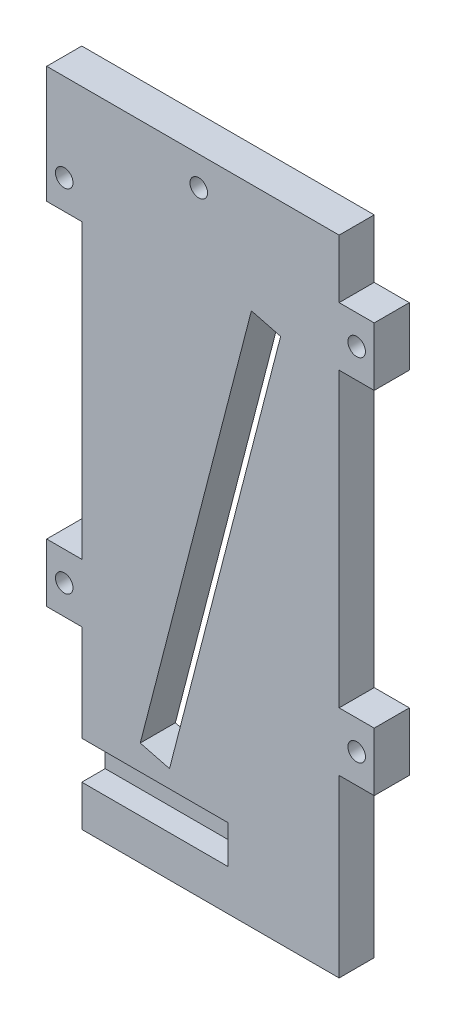
SolidWorks part; units mm, degrees
ref_plane "Plan de face" through (0, 0, 0) normal (0, 0, 1) x (1, 0, 0)
ref_plane "Plan de dessus" through (0, 0, 0) normal (0, 1, 0) x (1, 0, 0)
ref_plane "Plan de droite" through (0, 0, 0) normal (1, 0, 0) x (0, 0, -1)
sketch "Esquisse1" plane through (0, 0, 0) normal (0, 0, 1) x (1, 0, 0)
  line L0 (-6, 90) -> (-6, 70)
  line L1 (0, 0) -> (44, 0)
  line L2 (0, 0) -> (0, 10)
  line L3 (-6, 90) -> (44, 90)
  line L4 (44, 0) -> (44, 10)
  line L6 (44, 80) -> (44, 90)
  line L7 (0, 70) -> (-6, 70)
  line L9 (44, 80) -> (50, 80)
  line L10 (44, 20) -> (44, 70)
  line L11 (44, 70) -> (50, 70)
  line L12 (50, 80) -> (50, 70)
  line L13 (44, 10) -> (50, 10)
  line L14 (0, 20) -> (0, 70)
  line L15 (44, 20) -> (50, 20)
  line L16 (50, 10) -> (50, 20)
  line L17 (0, 10) -> (-6, 10)
  line L19 (0, 20) -> (-6, 20)
  line L20 (-6, 10) -> (-6, 20)
  dimension "D2" = 90
  dimension "D3" = 20
  dimension "D4" = 10
  dimension "D5" = 50
  dimension "D6" = 6
  dimension "D7" = 6
  dimension "D9" = 6
  dimension "D10" = 6
  dimension "D11" = 10
  dimension "D12" = 10
  dimension "D13" = 50
  dimension "D14" = 50
extrude "Boss.-Extru.1" add sketch "Esquisse1" along normal blind 6
sketch "Esquisse2" plane through (0, 0, 6) normal (0, 0, 1) x (1, 0, 0)
  line L1 (0, 10) -> (0, 0) construction
  line L2 (44, 90) -> (-6, 90) construction
  circle A0 centre (20, 85) radius 1.5
  dimension "D1" = 3
  dimension "D2" = 5
  dimension "D3" = 20
extrude "Enlèv. mat.-Extru.1" cut sketch "Esquisse2" against normal blind 6
sketch "Esquisse5" plane through (0, 0, 0) normal (0, 0, -1) x (-1, 0, 0)
  line L0 (6, 20) -> (6, 10) construction
  line L3 (0, 20) -> (6, 20) construction
  line L4 (-22, 90) -> (-22, 0) construction
  line L6 (0, 0) -> (-44, 0) construction
  line L8 (6, 90) -> (6, 70) construction
  line L9 (-44, 90) -> (6, 90) construction
  circle A0 centre (3, 75) radius 1.5
  circle A1 centre (3, 15) radius 1.5
  circle A2 centre (-47, 15) radius 1.5
  circle A3 centre (-47, 75) radius 1.5
  dimension "D1" = 3
  dimension "D2" = 3
  dimension "D4" = 3
  dimension "D5" = 15
  dimension "D6" = 5
  dimension "D3" = 3
extrude "Enlèv. mat.-Extru.6" cut sketch "Esquisse5" against normal blind 6
sketch "Esquisse6" plane through (0, 0, 0) normal (0, 0, -1) x (-1, 0, 0)
  line L0 (-22, 90) -> (-22, 0) construction
  line L2 (0, 0) -> (-44, 0) construction
  line L4 (-44, 90) -> (6, 90) construction
  circle A0 centre (3, 15) radius 2.995
  circle A1 centre (3, 75) radius 2.995
  circle A2 centre (-47, 75) radius 2.995
  circle A3 centre (-47, 15) radius 2.995
  dimension "D1" = 5.99
  dimension "D2" = 5.99
extrude "Enlèv. mat.-Extru.7" cut sketch "Esquisse6" against normal blind 3
sketch "Esquisse9" plane through (0, 0, 6) normal (0, 0, 1) x (1, 0, 0)
  line L1 (0, 0) -> (44, 0)
  line L2 (0, 0) -> (0, -20)
  line L3 (0, -20) -> (44, -20)
  line L4 (44, 0) -> (44, -20)
  dimension "D1" = 44
  dimension "D2" = 20
extrude "Boss.-Extru.3" add sketch "Esquisse9" against normal blind 6
sketch "Esquisse10" plane through (0, 0, 6) normal (0, 0, 1) x (1, 0, 0)
  line L0 (0, 10) -> (0, -20) construction
  line L1 (0, -13) -> (25, -13)
  line L2 (0, -13) -> (0, -6.5)
  line L3 (0, -6.5) -> (25, -6.5)
  line L4 (25, -13) -> (25, -6.5)
  line L5 (0, -20) -> (44, -20) construction
  dimension "D1" = 7
  dimension "D2" = 6.5
  dimension "D3" = 25
extrude "Enlèv. mat.-Extru.9" cut sketch "Esquisse10" against normal blind 4
sketch "Esquisse11" plane through (0, 0, 6) normal (0, 0, 1) x (1, 0, 0)
  line L0 (29, 71.2925) -> (10, -2.2075)
  line L1 (10, -2.2075) -> (15, -3.5)
  line L2 (15, -3.5) -> (34, 70)
  line L3 (34, 70) -> (29, 71.2925)
  line L4 (44, 90) -> (-6, 90) construction
  line L9 (44, 80) -> (44, 90) construction
  line L10 (44, 20) -> (44, 70) construction
  line L11 (0, 10) -> (0, -6.5) construction
  line L12 (25, -6.5) -> (0, -6.5) construction
  dimension "D1" = 10
  dimension "D2" = 15
  dimension "D3" = 10
  dimension "D4" = 3
  dimension "D5" = 20
extrude "Enlèv. mat.-Extru.11" cut sketch "Esquisse11" against normal blind 6
